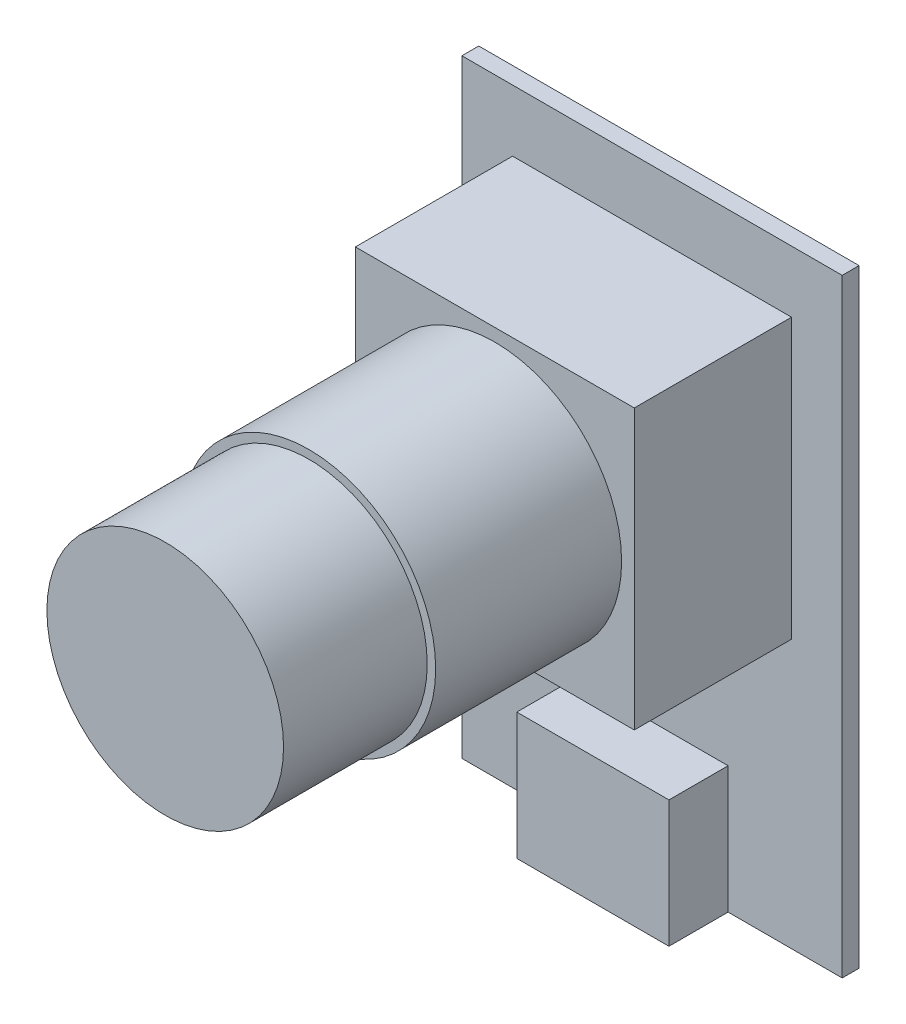
SolidWorks part; units mm, degrees
ref_plane "Front Plane" through (0, 0, 0) normal (0, 0, 1) x (1, 0, 0)
ref_plane "Top Plane" through (0, 0, 0) normal (0, 1, 0) x (1, 0, 0)
ref_plane "Right Plane" through (0, 0, 0) normal (1, 0, 0) x (0, 0, -1)
sketch "Sketch1" plane through (0, 0, 0) normal (0, 0, 1) x (1, 0, 0)
  line L1 (-11.25, 18) -> (11.25, 18)
  line L2 (-11.25, 18) -> (-11.25, -18)
  line L3 (-11.25, -18) -> (11.25, -18)
  line L4 (11.25, 18) -> (11.25, -18)
  line L5 (-11.25, 18) -> (11.25, -18) construction
  line L6 (-11.25, -18) -> (11.25, 18) construction
  point P0 (0, 0)
  dimension "D1" = 22.5
  dimension "D2" = 36
extrude "Boss-Extrude1" add sketch "Sketch1" along normal blind 1 contours L2 L3 L4 L1
sketch "Sketch2" plane through (0, 0, 1) normal (0, 0, 1) x (1, 0, 0)
  line L1 (-8.25, 14.3567) -> (8.25, 14.3567)
  line L2 (-8.25, 14.3567) -> (-8.25, -2.1433)
  line L3 (-8.25, -2.1433) -> (8.25, -2.1433)
  line L4 (8.25, 14.3567) -> (8.25, -2.1433)
  line L5 (-8.25, 14.3567) -> (8.25, -2.1433) construction
  line L6 (-8.25, -2.1433) -> (8.25, 14.3567) construction
  line L7 (-11.25, 18) -> (11.25, 18) construction
  point P0 (0, 6.1067)
  point P8 (0, 14.3567)
  point P10 (0, 18)
  dimension "D1" = 16.5
  dimension "D2" = 16.5
extrude "Boss-Extrude2" add sketch "Sketch2" along normal blind 9.3
sketch "Sketch3" plane through (0, 0, 10.3) normal (0, 0, 1) x (1, 0, 0)
  line L1 (8.25, 14.3567) -> (-8.25, 14.3567) construction
  line L2 (-8.25, 14.3567) -> (-8.25, -2.1433) construction
  circle A0 centre (0, 6.1067) radius 7.5
  point P7 (0, 14.3567)
  point P9 (-8.25, 6.1067)
  dimension "D1" = 15
extrude "Boss-Extrude3" add sketch "Sketch3" along normal blind 11
sketch "Sketch4" plane through (0, 0, 21.3) normal (0, 0, 1) x (1, 0, 0)
  circle A0 centre (0, 6.1067) radius 7
  dimension "D1" = 14
extrude "Boss-Extrude4" add sketch "Sketch4" along normal blind 8.5
sketch "Sketch5" plane through (0, 0, 1) normal (0, 0, 1) x (1, 0, 0)
  line L0 (-11.25, -18) -> (11.25, -18) construction
  line L1 (-4.5, -10.5) -> (4.5, -10.5)
  line L2 (-4.5, -10.5) -> (-4.5, -18)
  line L3 (-4.5, -18) -> (4.5, -18)
  line L4 (4.5, -10.5) -> (4.5, -18)
  line L5 (-4.5, -10.5) -> (4.5, -18) construction
  line L6 (-4.5, -18) -> (4.5, -10.5) construction
  point P0 (0, -14.25)
  point P8 (0, -18)
  dimension "D1" = 9
  dimension "D2" = 7.5
extrude "Boss-Extrude5" add sketch "Sketch5" along normal blind 3.5 contours L1 L4 L3 L2
sketch "Sketch7" plane through (0, 0, 0) normal (0, 0, -1) x (-1, 0, 0)
  line L0 (11.25, -18) -> (-11.25, -18) construction
  line L1 (-5.5, -2.4) -> (5.5, -2.4)
  line L2 (-5.5, -2.4) -> (-5.5, -18)
  line L3 (-5.5, -18) -> (5.5, -18)
  line L4 (5.5, -2.4) -> (5.5, -18)
  line L5 (-5.5, -2.4) -> (5.5, -18) construction
  line L6 (-5.5, -18) -> (5.5, -2.4) construction
  point P0 (0, -10.2)
  point P8 (0, -18)
  dimension "D1" = 11
  dimension "D2" = 15.6
extrude "Boss-Extrude6" add sketch "Sketch7" along normal blind 2 contours L1 L4 L3 L2
